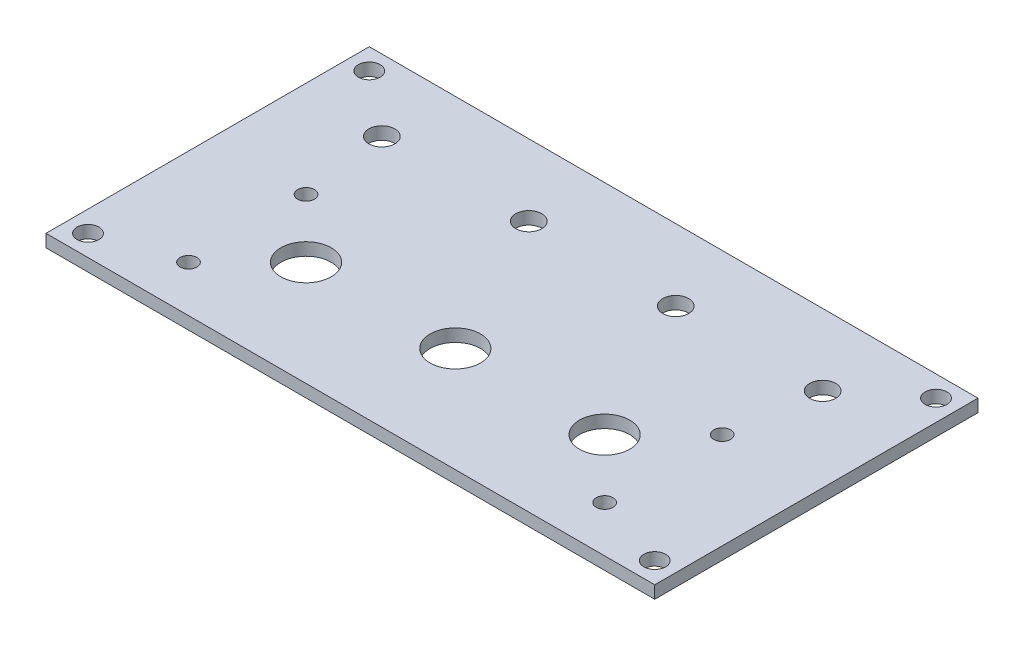
SolidWorks part; units mm, degrees
ref_plane "Front Plane" through (0, 0, 0) normal (0, 0, 1) x (1, 0, 0)
ref_plane "Top Plane" through (0, 0, 0) normal (0, 1, 0) x (1, 0, 0)
ref_plane "Right Plane" through (0, 0, 0) normal (1, 0, 0) x (0, 0, -1)
sketch "Sketch1" plane through (0, 0, 0) normal (0, 1, 0) x (1, 0, 0)
  line L0 (20, 60) -> (36.94, 60) construction
  line L1 (0, 0) -> (145, 0)
  line L2 (0, 0) -> (0, 77)
  line L3 (0, 77) -> (145, 77)
  line L4 (145, 0) -> (145, 77)
  line L5 (12.5, 47) -> (27.5, 47)
  line L6 (12.5, 47) -> (12.5, 56)
  line L7 (12.5, 56) -> (27.5, 56)
  line L8 (27.5, 47) -> (27.5, 56)
  line L9 (125, 60) -> (108.06, 60) construction
  circle A0 centre (20, 60) radius 3.1
  circle A1 centre (55, 60) radius 3.1
  circle A2 centre (90, 60) radius 3.1
  circle A3 centre (125, 60) radius 3.1
  circle A4 centre (5, 72) radius 2.6
  circle A5 centre (5, 5) radius 2.6
  circle A6 centre (140, 5) radius 2.6
  circle A7 centre (140, 72) radius 2.6
  circle A8 centre (20, 60) radius 8.5
  circle A9 centre (55, 60) radius 8.5
  circle A10 centre (90, 60) radius 8.5
  circle A11 centre (125, 60) radius 8.5
  circle A12 centre (36.94, 25) radius 6
  circle A13 centre (72.5, 25) radius 6
  circle A14 centre (108.06, 25) radius 6
  circle A15 centre (22.94, 39) radius 2
  circle A16 centre (122.06, 39) radius 2
  circle A17 centre (122.06, 11) radius 2
  circle A18 centre (22.94, 11) radius 2
  point P44 (0, 0)
  dimension "D1" = 6.2
  dimension "D2" = 6.2
  dimension "D3" = 6.2
  dimension "D4" = 6.2
  dimension "D5" = 5.2
  dimension "D6" = 5.2
  dimension "D7" = 5.2
  dimension "D8" = 5.2
  dimension "D17" = 17
  dimension "D21" = 17
  dimension "D22" = 17
  dimension "D23" = 17
  dimension "D24" = 12
  dimension "D25" = 12
  dimension "D26" = 12
  dimension "D46" = 4
  dimension "D47" = 4
  dimension "D48" = 4
  dimension "D49" = 4
  dimension "D9" = 5
  dimension "D10" = 5
  dimension "D11" = 5
  dimension "D12" = 5
  dimension "D13" = 5
  dimension "D14" = 5
  dimension "D15" = 5
  dimension "D16" = 5
  dimension "D18" = 13
  dimension "D19" = 15
  dimension "D20" = 7.5
  dimension "D27" = 17
  dimension "D28" = 20
  dimension "D29" = 35
  dimension "D30" = 17
  dimension "D31" = 35
  dimension "D32" = 17
  dimension "D33" = 35
  dimension "D34" = 17
  dimension "D35" = 35
  dimension "D36" = 77
  dimension "D37" = 35.56
  dimension "D38" = 35.56
  dimension "D40" = 25
  dimension "D41" = 14
  dimension "D42" = 20
  dimension "D43" = 14
  dimension "D44" = 14
  dimension "D45" = 14
  dimension "D50" = 14
  dimension "D51" = 14
  dimension "D52" = 14
  dimension "D53" = 14
extrude "Boss-Extrude1" add sketch "Sketch1" along normal blind 3 contours L1 L4 L3 L2 A14 A13 A12 A11 A10 A9 A8 L8 L5 L6 A7 A6 A5 A4 | A8 L6 L5 L8 | L7 A8 | L7 A8 A0 | A9 A1 | A10 A2 | A11 A3
